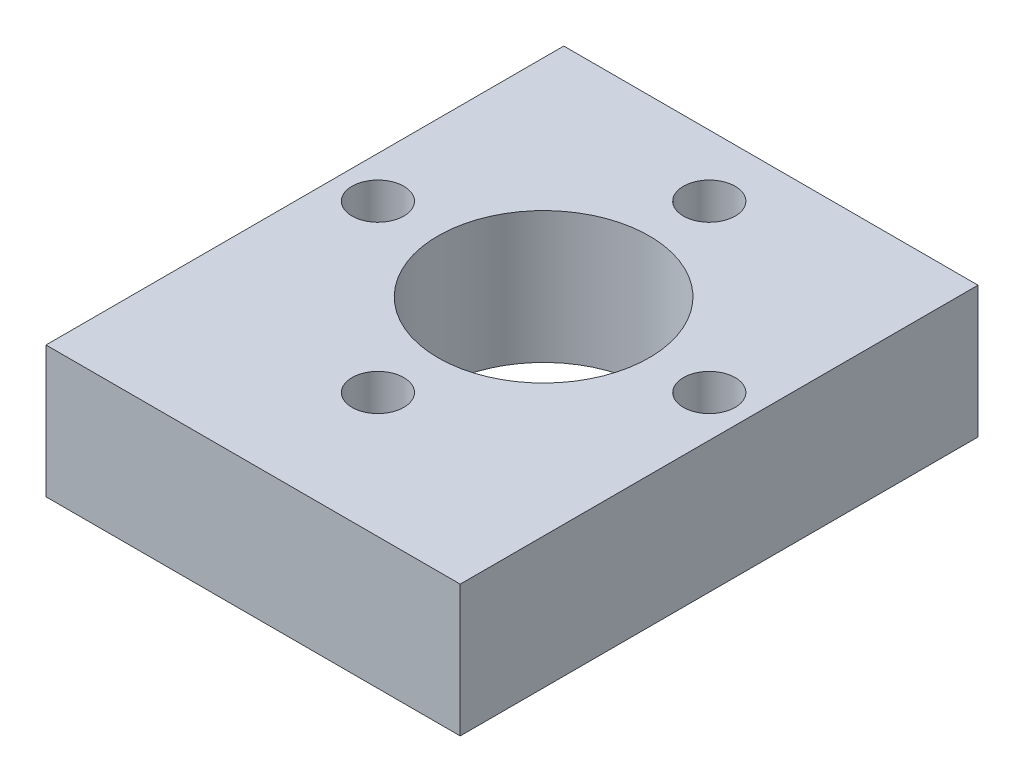
SolidWorks part; units mm, degrees
ref_plane "Front Plane" through (0, 0, 0) normal (0, 0, 1) x (1, 0, 0)
ref_plane "Top Plane" through (0, 0, 0) normal (0, 1, 0) x (1, 0, 0)
ref_plane "Right Plane" through (0, 0, 0) normal (1, 0, 0) x (0, 0, -1)
sketch "Sketch1" plane through (0, 0, 0) normal (0, 1, 0) x (1, 0, 0)
  line L1 (-10, -12.5) -> (10, -12.5)
  line L2 (-10, -12.5) -> (-10, 12.5)
  line L3 (-10, 12.5) -> (10, 12.5)
  line L4 (10, -12.5) -> (10, 12.5)
  line L5 (-10, -12.5) -> (10, 12.5) construction
  line L6 (-10, 12.5) -> (10, -12.5) construction
  circle A0 centre (0, 1.5262) radius 5.1
  point P0 (0, 1.5262)
  dimension "D1" = 10.2
  dimension "D2" = 20
  dimension "D3" = 25
  dimension "D4" = 1.5262
extrude "Boss-Extrude1" add sketch "Sketch1" along normal blind 6.35 contours L1 L4 L3 L2 A0
sketch "Sketch2" plane through (0, 6.35, 0) normal (0, 1, 0) x (1, 0, 0)
  circle A0 centre (0, 1.5262) radius 8 construction
  point P2 (0, 9.5262)
  point P4 (8, 1.5262)
  point P5 (0, -6.4738)
  point P6 (-8, 1.5262)
  dimension "D1" = 8
hole_wizard "Tap Drill for M3x0.5 Tap1" positions "Sketch2" profile "Sketch3" hole size "M3x0.5" standard "ANSI Metric" end condition through all
sketch "Sketch3" plane through (-8, 6.35, -1.5262) normal (1, 0, 0) x (0, 0, 1)
  line L0 (0, 0) -> (0, 6.35)
  line L1 (0, 6.35) -> (1.25, 6.35)
  line L2 (1.25, 6.35) -> (1.25, 0)
  line L5 (1.25, 0) -> (0, 0)
  line L11 (0, -6.35) -> (0, 107.95) construction
  dimension "Thru Hole Dia." = 2.5
  dimension "Thru Hole Depth" = 6.35
sketch "Sketch4" plane through (0, 0, -12.5) normal (0, 0, -1) x (-1, 0, 0)
  line L0 (0, 0) -> (0, 6.35) construction
  line L1 (10, 6.35) -> (-10, 6.35) construction
  line L9 (-7, 3.175) -> (7, 3.175) construction
  point P5 (0, 3.175)
  point P47 (0, 3.175)
  dimension "D1" = 14
hole_wizard "Tap Drill for M3x0.5 Tap3" positions "Sketch7" profile "Sketch8" hole size "M3x0.5" standard "ANSI Metric"
sketch "Sketch7" plane through (0, 0, -12.5) normal (0, 0, -1) x (-1, 0, 0)
  point P0 (-7, 3.175)
  point P3 (7, 3.175)
sketch "Sketch8" plane through (7, 3.175, -12.5) normal (1, 0, 0) x (0, 1, 0)
  line L0 (0, 0) -> (0, 6.7511)
  line L1 (0, 6.7511) -> (1.25, 6)
  line L2 (1.25, 6) -> (1.25, 0)
  line L5 (1.25, 0) -> (0, 0)
  line L10 (0, 6.7511) -> (-1.25, 6) construction
  line L11 (0, -6.35) -> (0, 107.95) construction
  dimension "Hole Dia." = 2.5
  dimension "Hole Depth" = 6
  dimension "Drill Angle" = 118
